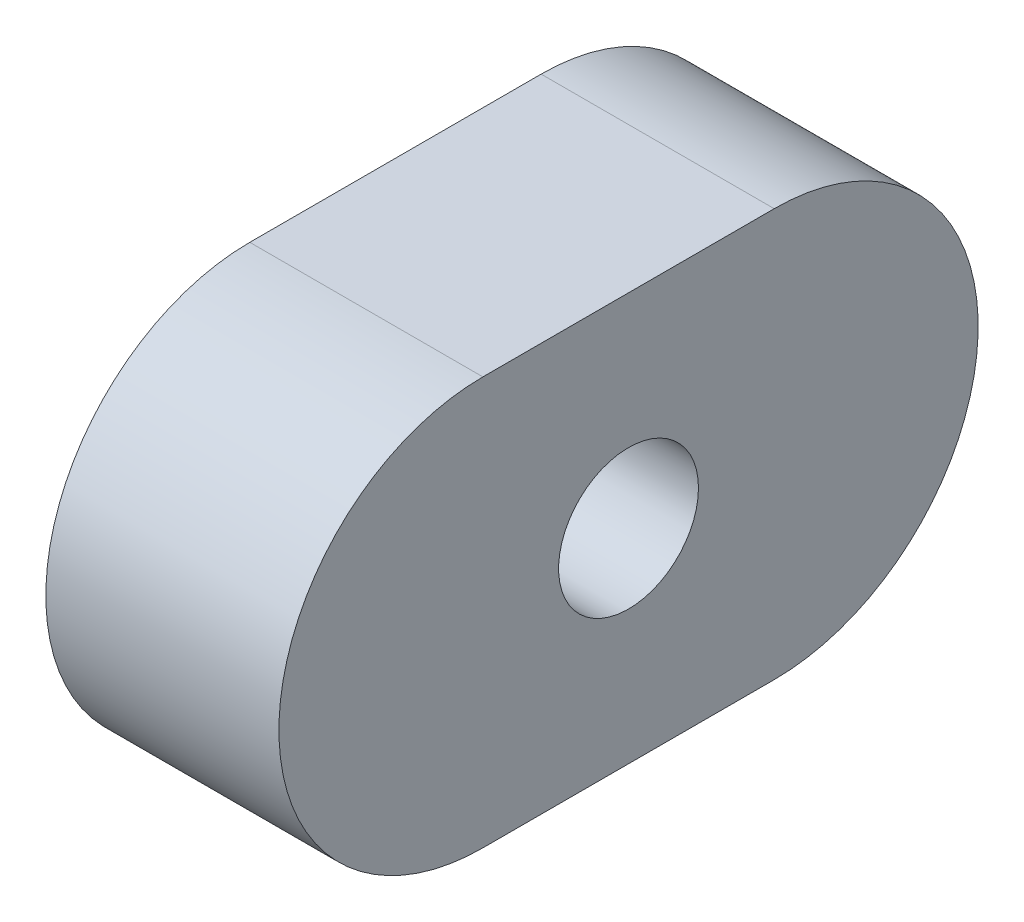
SolidWorks part; units mm, degrees
ref_plane "Front Plane" through (0, 0, 0) normal (0, 0, 1) x (1, 0, 0)
ref_plane "Top Plane" through (0, 0, 0) normal (0, 1, 0) x (1, 0, 0)
ref_plane "Right Plane" through (0, 0, 0) normal (1, 0, 0) x (0, 0, -1)
sketch "Sketch1" plane through (0, 0, 0) normal (1, 0, 0) x (0, 0, -1)
  line L0 (12.5, 0) -> (-12.5, 0) construction
  line L1 (12.5, -17.5) -> (-12.5, -17.5)
  line L2 (12.5, 17.5) -> (-12.5, 17.5)
  arc A0 (12.5, -17.5) -> (12.5, 17.5) centre (12.5, 0) ccw
  arc A1 (-12.5, 17.5) -> (-12.5, -17.5) centre (-12.5, 0) ccw
  circle A2 centre (0, 0) radius 6
  point P2 (0, 0)
  dimension "D3" = 12
  dimension "D1" = 35
  dimension "D2" = 25
extrude "Boss-Extrude1" add sketch "Sketch1" along normal mid plane 20
equation "\"WheelDiameter\" = 150mm"
equation "\"WheelRadius\" = \"WheelDiameter\" / 2"
equation "\"DT_WheelWidth\" = 45mm"
equation "\"DT_Wheelbase\" = 300mm"
equation "\"DT_ShaftDiameter\" = 12mm"
equation "\"DT_FrontShaftLength\" = 180mm"
equation "\"DT_RearShaftLength\" = 200mm"
equation "\"DT_BearingWidth\" = 20mm"
equation "\"DT_BearingHousingWidth\"= 60mm"
equation "\"DT_BearingHousingHeight\" = 35mm"
equation "\"DT_ChainPitch\" = 9.525mm"
equation "\"DT_SprocketTeeth\" = 18"
equation "\"DT_SprocketPitchDiameter\" = 54.851mm"
equation "\"DT_SprocketOuterDiameter\" = 60mm"
equation "\"DT_SprocketThickness\" = 6mm"
equation "\"DT_SprocketHubDiameter\" = 25mm"
equation "\"DT_SprocketHubLength\" = 20mm"
equation "\"DT_CouplingDiameter\" = 30mm"
equation "\"DT_CouplingLength\" = 35mm"
equation "\"DT_MotorDiameter\" = 60mm"
equation "\"DT_MotorLength\" = 120mm"
equation "\"DT_MotorShaftDiameter\" = 8mm"
equation "\"DT_MotorShaftLength\" = 20mm"
